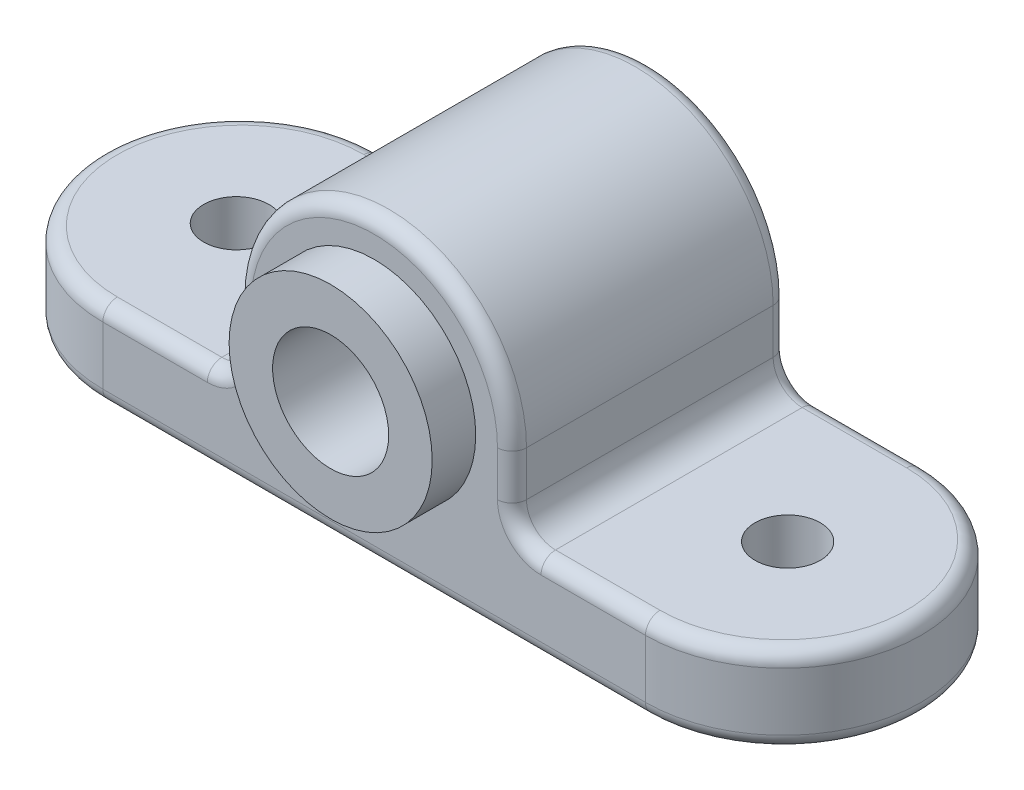
SolidWorks part; units mm, degrees
material "Zinc AC41A Alloy, As Cast"
ref_plane "Front Plane" through (0, 0, 0) normal (0, 0, 1) x (1, 0, 0)
ref_plane "Top Plane" through (0, 0, 0) normal (0, 1, 0) x (1, 0, 0)
ref_plane "Right Plane" through (0, 0, 0) normal (1, 0, 0) x (0, 0, -1)
sketch "Sketch1" plane through (0, 0, 0) normal (0, 0, 1) x (1, 0, 0)
  line L0 (-28.2, 0) -> (28.2, 0)
  line L1 (28.2, 0) -> (28.2, 6)
  line L2 (28.2, 6) -> (11.5, 6)
  line L3 (9.5, 11.1) -> (9.5, 8)
  line L4 (0, 0) -> (0, 20.6) construction
  line L5 (-9.5, 11.1) -> (-9.5, 8)
  line L6 (-28.2, 6) -> (-11.5, 6)
  line L7 (-28.2, 0) -> (-28.2, 6)
  circle A0 centre (0, 11.1) radius 4
  arc A1 (9.5, 11.1) -> (-9.5, 11.1) centre (0, 11.1) ccw
  arc A2 (9.5, 8) -> (11.5, 6) centre (11.5, 8) ccw
  arc A3 (-9.5, 8) -> (-11.5, 6) centre (-11.5, 8) cw
  dimension "D4" = 8
  dimension "D5" = 11.1
  dimension "D6" = 19
  dimension "D3" = 2
  dimension "D1" = 6
  dimension "D2" = 28.2
extrude "Boss-Extrude1" add sketch "Sketch1" along normal blind 19
sketch "Sketch2" plane through (0, 0, 0) normal (0, -1, 0) x (1, 0, 0)
  line L0 (-28.2, 0) -> (28.2, 0) construction
  line L1 (-28.2, 19) -> (28.2, 19) construction
  line L2 (18.7, 19) -> (-18.7, 19)
  line L3 (18.7, 0) -> (-18.7, 0)
  line L5 (-19, 9.5) -> (19, 9.5)
  line L7 (28.2, 19) -> (28.2, 0) construction
  line L8 (-28.2, 19) -> (-28.2, 0) construction
  arc A0 (-18.7, 0) -> (-18.7, 19) centre (-18.7, 9.5) cw
  arc A1 (18.7, 0) -> (18.7, 19) centre (18.7, 9.5) ccw
  circle A2 centre (-19, 9.5) radius 2.25
  circle A3 centre (19, 9.5) radius 2.25
  point P18 (0, 9.5)
  dimension "D1" = 4.5
  dimension "D2" = 38
extrude "Cut-Extrude2" cut sketch "Sketch2" against normal blind 19
sketch "Sketch3" plane through (0, 0, 19) normal (0, 0, 1) x (1, 0, 0)
  circle A0 centre (0, 11.1) radius 7
  circle A1 centre (0, 11.1) radius 4 construction
  circle A2 centre (0, 11.1) radius 4
  dimension "D1" = 14
extrude "Boss-Extrude2" add sketch "Sketch3" along normal blind 3
fillet "Fillet1" radius 1 20 edges at (10.0858, 6.5858, 0) (9.5, 9.55, 0) (0, 20.6, 0) (-9.5, 9.55, 0) (-10.0858, 6.5858, 0) (-15.1, 6, 0) (-28.2, 6, 9.5) (-15.1, 6, 19) (-10.0858, 6.5858, 19) (-9.5, 9.55, 19) (0, 20.6, 19) (9.5, 9.55, 19) (10.0858, 6.5858, 19) (-28.2, 0, 9.5) (0, 0, 19) (28.2, 0, 9.5) (0, 0, 0) (15.1, 6, 19) (15.1, 6, 0) (28.2, 6, 9.5)
